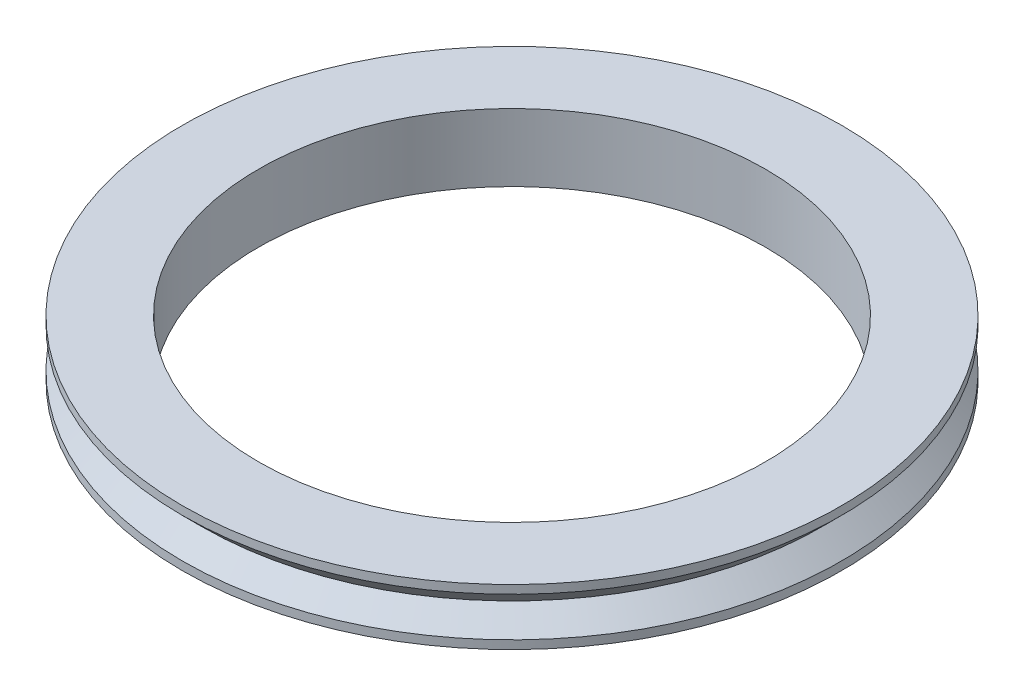
SolidWorks part; units mm, degrees
material "Alliage 1060"
ref_plane "Plan de face" through (0, 0, 0) normal (0, 0, 1) x (1, 0, 0)
ref_plane "Plan de dessus" through (0, 0, 0) normal (0, 1, 0) x (1, 0, 0)
ref_plane "Plan de droite" through (0, 0, 0) normal (1, 0, 0) x (0, 0, -1)
sketch "Esquisse1" plane through (0, 0, 0) normal (0, 0, 1) x (1, 0, 0)
  line L0 (0, 68.2015) -> (0, -43.8949) construction
  line L1 (22.5, 0) -> (24.5, 0)
  line L2 (29.25, 1) -> (29.25, 1.75)
  line L3 (29.25, 1.75) -> (27.5, 3.5)
  line L4 (27.5, 3.5) -> (29.25, 5.25)
  line L5 (29.25, 5.25) -> (29.25, 6)
  line L6 (29.25, 6) -> (22.5, 6)
  line L7 (22.5, 6) -> (22.5, 0)
  line L9 (22.5, -6.9) -> (22.5, -0.1) construction
  line L10 (24.5, 0) -> (24.5, 1)
  line L11 (24.5, 1) -> (29.25, 1)
  dimension "D1" = 5
  dimension "D2" = 5
  dimension "D3" = 3.5
  dimension "D4" = 55
  dimension "D5" = 2
  dimension "D6" = 1
revolve "Révolution1" add sketch "Esquisse1" angle 360 about L0
